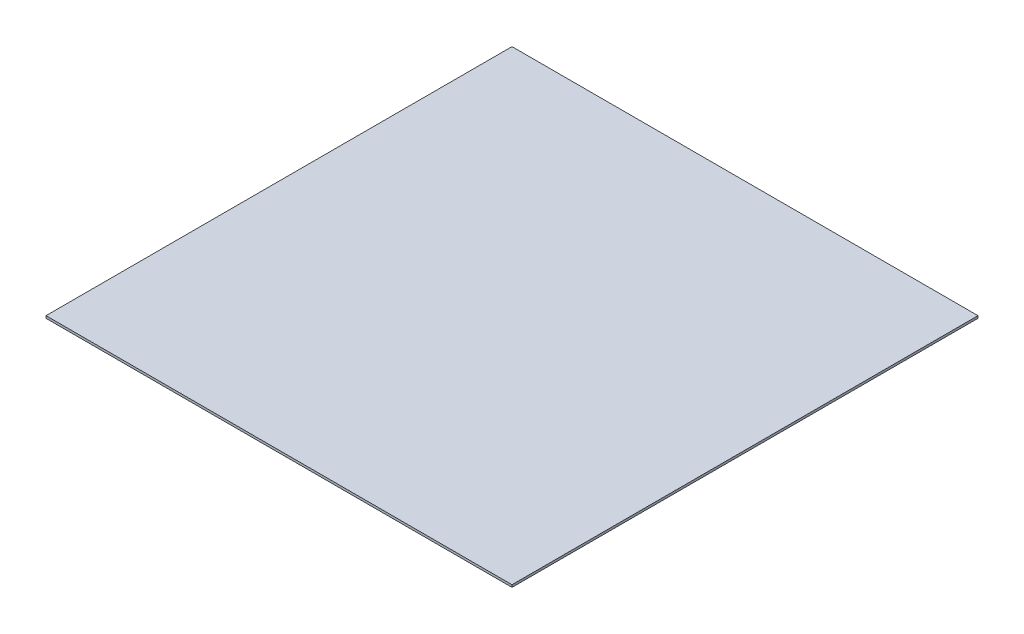
SolidWorks part; units mm, degrees
ref_plane "Front Plane" through (0, 0, 0) normal (0, 0, 1) x (1, 0, 0)
ref_plane "Top Plane" through (0, 0, 0) normal (0, 1, 0) x (1, 0, 0)
ref_plane "Right Plane" through (0, 0, 0) normal (1, 0, 0) x (0, 0, -1)
sketch "Sketch1" plane through (0, 0, 0) normal (0, 1, 0) x (1, 0, 0)
  line L1 (-254, -254) -> (254, -254)
  line L2 (-254, -254) -> (-254, 254)
  line L3 (-254, 254) -> (254, 254)
  line L4 (254, -254) -> (254, 254)
  line L5 (-254, -254) -> (254, 254) construction
  line L6 (-254, 254) -> (254, -254) construction
  point P0 (0, 0)
  dimension "D1" = 508
  dimension "D2" = 508
extrude "Ground Plane" add sketch "Sketch1" along normal blind 2.54 contours L3 L4 L1 L2
